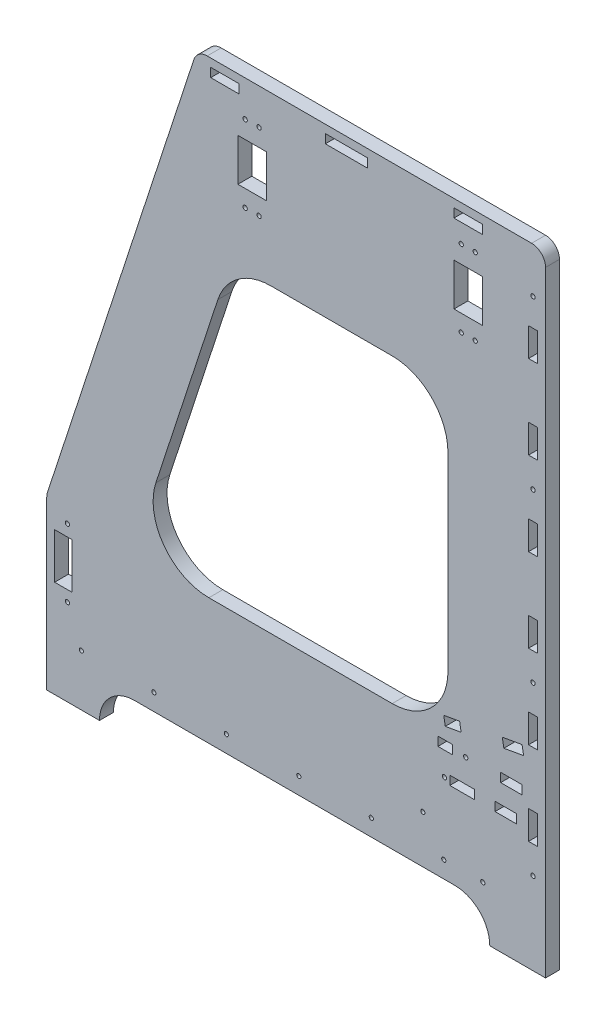
SolidWorks part; units mm, degrees
ref_plane "Płaszczyzna przednia" through (0, 0, 0) normal (0, 0, 1) x (1, 0, 0)
ref_plane "Płaszczyzna górna" through (0, 0, 0) normal (0, 1, 0) x (1, 0, 0)
ref_plane "Płaszczyzna prawa" through (0, 0, 0) normal (1, 0, 0) x (0, 0, -1)
ref_plane "Płaszczyzna1" through (0, 0, -20) normal (0, 0, 1) x (1, 0, 0)
sketch "Szkic1" plane through (0, 0, -20) normal (0, 0, 1) x (1, 0, 0)
  line L0 (-250.3685, -57.104) -> (-250.3685, -508.604)
  line L1 (-250.3685, -57.104) -> (-608.3685, -57.104)
  line L2 (-250.3685, -508.604) -> (-608.3685, -508.604)
  line L3 (-608.3685, -57.104) -> (-608.3685, -508.604)
  point P0 (0, 0)
  dimension "D1" = 358
  dimension "D2" = 451.5
  dimension "D3" = 250.3685
extrude "Dodanie-wyciągnięcie1" add sketch "Szkic1" along normal blind 10
sketch "Szkic2" plane through (0, 0, -20) normal (0, 0, -1) x (-1, 0, 0)
  line L0 (608.3685, -387.604) -> (502.6212, -63.9978)
  line L1 (608.3685, -57.104) -> (608.3685, -508.604) construction
  line L2 (500.3685, -57.104) -> (493.1159, -57.104)
  line L3 (250.3685, -57.104) -> (608.3685, -57.104) construction
  line L4 (500.3685, -57.104) -> (608.3685, -57.104)
  line L5 (608.3685, -57.104) -> (608.3685, -387.604)
  line L6 (250.3685, -508.604) -> (250.3685, -57.104) construction
  line L7 (608.3685, -508.604) -> (250.3685, -508.604) construction
  arc A0 (502.6212, -63.9978) -> (493.1159, -57.104) centre (493.1159, -67.104) ccw
  dimension "D3" = 10
  dimension "D1" = 250
  dimension "D2" = 121
  dimension "D4" = 71.904
extrude "Wytnij-wyciągnięcie1" cut sketch "Szkic2" against normal blind 10
sketch "Szkic3" plane through (0, 0, -10) normal (0, 0, 1) x (1, 0, 0)
  line L0 (-608.3685, -508.604) -> (-250.3685, -508.604) construction
  line L1 (-570.3685, -508.604) -> (-290.3685, -508.604)
  line L4 (-545.3685, -483.604) -> (-315.3685, -483.604)
  arc A0 (-570.3685, -508.604) -> (-545.3685, -483.604) centre (-545.3685, -508.604) cw
  arc A1 (-315.3685, -483.604) -> (-290.3685, -508.604) centre (-315.3685, -508.604) cw
extrude "Wytnij-wyciągnięcie2" cut sketch "Szkic3" against normal blind 10
sketch "Szkic4" plane through (0, 0, -10) normal (0, 0, 1) x (1, 0, 0)
  line L0 (-491.8908, -393.104) -> (-360.3685, -393.104)
  line L1 (-250.3685, -508.604) -> (-250.3685, -57.104) construction
  line L2 (-320.3685, -353.104) -> (-320.3685, -217.104)
  line L3 (-447.4491, -177.104) -> (-360.3685, -177.104)
  line L4 (-529.9123, -340.6794) -> (-485.4705, -204.6794)
  line L9 (-315.3685, -483.604) -> (-545.3685, -483.604) construction
  line L10 (-250.3685, -57.104) -> (-493.1159, -57.104) construction
  line L12 (-502.6212, -63.9978) -> (-608.3685, -387.604) construction
  arc A0 (-360.3685, -393.104) -> (-320.3685, -353.104) centre (-360.3685, -353.104) ccw
  arc A1 (-529.9123, -340.6794) -> (-491.8908, -393.104) centre (-491.8908, -353.104) ccw
  arc A2 (-320.3685, -217.104) -> (-360.3685, -177.104) centre (-360.3685, -217.104) ccw
  arc A3 (-485.4705, -204.6794) -> (-447.4491, -177.104) centre (-447.4491, -217.104) cw
  dimension "D5" = 40
  dimension "D1" = 70
  dimension "D2" = 90.5
  dimension "D3" = 120
  dimension "D4" = 60
extrude "Wytnij-wyciągnięcie3" cut sketch "Szkic4" against normal blind 10
sketch "Szkic5" plane through (0, 0, -10) normal (0, 0, 1) x (1, 0, 0)
  line L0 (-262.3685, -109.604) -> (-256.3685, -109.604)
  line L1 (-262.3685, -129.604) -> (-256.3685, -129.604)
  line L2 (-262.3685, -129.604) -> (-262.3685, -109.604)
  line L3 (-256.3685, -129.604) -> (-256.3685, -109.604)
  line L4 (-256.3685, -109.604) -> (-262.3685, -109.604)
  line L5 (-256.3685, -109.604) -> (-262.3685, -109.604)
  line L6 (-262.3685, -109.604) -> (-262.3685, -129.604)
  line L7 (-262.3685, -109.604) -> (-262.3685, -129.604)
  line L9 (-262.3685, -129.604) -> (-256.3685, -129.604)
  line L10 (-262.3685, -129.604) -> (-256.3685, -129.604)
  line L11 (-256.3685, -129.604) -> (-256.3685, -109.604)
  line L12 (-262.5685, -129.804) -> (-262.5685, -109.404)
  line L13 (-262.5685, -109.404) -> (-256.1685, -109.404)
  line L14 (-256.1685, -129.804) -> (-256.1685, -109.404)
  line L15 (-262.5685, -129.804) -> (-256.1685, -129.804)
  line L24 (-256.3685, -129.604) -> (-256.3685, -109.604)
  line L49 (-256.3685, -109.604) -> (-256.3685, -91.154) construction
  line L50 (-262.3685, -109.604) -> (-262.3685, -91.154) construction
  line L51 (-256.3685, -109.604) -> (-256.3685, -91.154)
  line L52 (-262.3685, -109.604) -> (-262.3685, -91.154)
  dimension "D1" = 0
  dimension "D4" = 0.2
sketch "Szkic8" plane through (0, 0, -10) normal (0, 0, 1) x (1, 0, 0)
  line L0 (-262.5685, -109.404) -> (-256.1685, -109.404) construction
  line L1 (-262.5685, -129.804) -> (-262.5685, -109.404) construction
  line L2 (-256.1685, -129.804) -> (-256.1685, -109.404) construction
  line L3 (-262.5685, -129.804) -> (-256.1685, -129.804) construction
  line L4 (-262.5685, -109.404) -> (-256.1685, -109.404)
  line L5 (-262.5685, -129.804) -> (-262.5685, -109.404)
  line L6 (-256.1685, -129.804) -> (-256.1685, -109.404)
  line L7 (-262.5685, -129.804) -> (-256.1685, -129.804)
extrude "Wytnij-wyciągnięcie4" cut sketch "Szkic8" against normal blind 10
pattern_linear "Szyk liniowy1" count 6 spacing 60 along (0, -1, 0) of "Wytnij-wyciągnięcie4"
sketch "Szkic33" plane through (0, 0, -10) normal (0, 0, 1) x (1, 0, 0)
  line L0 (-262.3685, -88.054) -> (-256.3685, -88.054) construction
  line L1 (-262.3685, -91.154) -> (-256.3685, -91.154) construction
  line L2 (-262.3685, -88.054) -> (-256.3685, -88.054)
  line L3 (-262.3685, -91.154) -> (-256.3685, -91.154)
  line L4 (-259.3685, -88.054) -> (-259.3685, -91.154)
  circle A0 centre (-259.3685, -89.604) radius 1.55
  dimension "D1" = 3.1
sketch "Szkic9" plane through (0, 0, -10) normal (0, 0, 1) x (1, 0, 0)
  circle A0 centre (-259.3685, -89.604) radius 1.55 construction
  circle A1 centre (-259.3685, -89.604) radius 1.55
extrude "Wytnij-wyciągnięcie5" cut sketch "Szkic9" against normal blind 10
pattern_linear "Szyk liniowy2" count 4 spacing 120 along (0, -1, 0) of "Wytnij-wyciągnięcie5"
sketch "Szkic11" plane through (0, 0, -10) normal (0, 0, 1) x (1, 0, 0)
  line L0 (-602.5685, -406.124) -> (-602.5685, -438.804)
  line L1 (-602.3685, -406.324) -> (-590.3685, -406.324)
  line L2 (-602.5685, -438.804) -> (-590.1685, -438.804)
  line L3 (-590.3685, -438.604) -> (-590.3685, -406.324) construction
  line L4 (-590.1685, -438.804) -> (-590.1685, -406.124)
  line L5 (-602.3685, -438.604) -> (-590.3685, -438.604)
  line L6 (-590.3685, -438.604) -> (-590.3685, -406.324)
  line L8 (-250.3685, -57.104) -> (-493.1159, -57.104)
  line L9 (-596.3685, -445.004) -> (-590.3685, -445.004) construction
  line L10 (-502.6212, -63.9978) -> (-608.3685, -387.604)
  line L11 (-608.3685, -387.604) -> (-608.3685, -508.604)
  line L12 (-608.3685, -508.604) -> (-570.3685, -508.604)
  line L13 (-545.3685, -483.604) -> (-315.3685, -483.604)
  line L14 (-290.3685, -508.604) -> (-250.3685, -508.604)
  line L15 (-250.3685, -508.604) -> (-250.3685, -57.104)
  line L16 (-250.3685, -57.104) -> (-493.1159, -57.104)
  line L17 (-590.3685, -448.104) -> (-596.3685, -448.104) construction
  line L18 (-502.6212, -63.9978) -> (-608.3685, -387.604)
  line L19 (-608.3685, -387.604) -> (-608.3685, -508.604)
  line L20 (-608.3685, -508.604) -> (-570.3685, -508.604)
  line L21 (-545.3685, -483.604) -> (-315.3685, -483.604)
  line L22 (-290.3685, -508.604) -> (-250.3685, -508.604)
  line L23 (-250.3685, -508.604) -> (-250.3685, -57.104)
  line L28 (-596.3685, -396.324) -> (-590.3685, -396.324) construction
  line L29 (-590.3685, -399.424) -> (-596.3685, -399.424) construction
  line L30 (-602.3685, -406.324) -> (-602.3685, -438.604)
  line L32 (-596.3685, -396.324) -> (-590.3685, -396.324)
  line L33 (-590.3685, -399.424) -> (-596.3685, -399.424)
  line L34 (-596.3685, -445.004) -> (-590.3685, -445.004)
  line L35 (-590.3685, -448.104) -> (-596.3685, -448.104)
  line L36 (-593.3685, -396.324) -> (-593.3685, -399.424)
  line L37 (-593.3685, -445.004) -> (-593.3685, -448.104)
  line L46 (-602.5685, -406.124) -> (-590.1685, -406.124)
  circle A1 centre (-593.3685, -397.874) radius 1.55
  circle A2 centre (-593.3685, -446.554) radius 1.55
  arc A6 (-545.3685, -483.604) -> (-570.3685, -508.604) centre (-545.3685, -508.604) ccw
  arc A7 (-290.3685, -508.604) -> (-315.3685, -483.604) centre (-315.3685, -508.604) ccw
  arc A10 (-545.3685, -483.604) -> (-570.3685, -508.604) centre (-545.3685, -508.604) ccw
  arc A11 (-290.3685, -508.604) -> (-315.3685, -483.604) centre (-315.3685, -508.604) ccw
  arc A17 (-493.1159, -57.104) -> (-502.6212, -63.9978) centre (-493.1159, -67.104) ccw
  arc A18 (-493.1159, -57.104) -> (-502.6212, -63.9978) centre (-493.1159, -67.104) ccw
  point P21 (-596.5685, -406.124)
  point P22 (-596.5685, -438.804)
  dimension "D3" = 3.1
  dimension "D4" = 3.1
  dimension "D2" = 12
  dimension "D1" = 0
sketch "Szkic12" plane through (0, 0, -10) normal (0, 0, 1) x (1, 0, 0)
  line L4 (-602.5685, -406.124) -> (-590.1685, -406.124) construction
  line L5 (-590.1685, -438.804) -> (-590.1685, -406.124) construction
  line L6 (-602.5685, -438.804) -> (-590.1685, -438.804) construction
  line L7 (-602.5685, -406.124) -> (-602.5685, -438.804) construction
  line L8 (-602.5685, -406.124) -> (-590.1685, -406.124)
  line L9 (-590.1685, -438.804) -> (-590.1685, -406.124)
  line L10 (-602.5685, -438.804) -> (-590.1685, -438.804)
  line L11 (-602.5685, -406.124) -> (-602.5685, -438.804)
extrude "Wytnij-wyciągnięcie7" cut sketch "Szkic12" against normal blind 10
sketch "Szkic13" plane through (0, 0, -10) normal (0, 0, 1) x (1, 0, 0)
  circle A1 centre (-593.3685, -397.874) radius 1.55 construction
  circle A2 centre (-593.3685, -446.554) radius 1.55 construction
  circle A3 centre (-593.3685, -397.874) radius 1.55
  circle A4 centre (-593.3685, -446.554) radius 1.55
extrude "Wytnij-wyciągnięcie8" cut sketch "Szkic13" against normal blind 10
sketch "Szkic15" plane through (0, 0, -10) normal (0, 0, 1) x (1, 0, 0)
  circle A0 centre (-295.3685, -471.604) radius 1.5 construction
  circle A1 centre (-323.3685, -471.604) radius 1.5 construction
  circle A2 centre (-375.3685, -471.604) radius 1.5 construction
  circle A3 centre (-427.3685, -471.604) radius 1.5 construction
  circle A4 centre (-531.3685, -471.604) radius 1.5 construction
  circle A5 centre (-479.3685, -471.604) radius 1.5 construction
  circle A6 centre (-583.3685, -471.604) radius 1.5 construction
  circle A7 centre (-338.3685, -449.4127) radius 1.5 construction
  circle A8 centre (-295.3685, -471.604) radius 1.5
  circle A9 centre (-323.3685, -471.604) radius 1.5
  circle A10 centre (-375.3685, -471.604) radius 1.5
  circle A11 centre (-427.3685, -471.604) radius 1.5
  circle A12 centre (-531.3685, -471.604) radius 1.5
  circle A13 centre (-479.3685, -471.604) radius 1.5
  circle A14 centre (-583.3685, -471.604) radius 1.5
  circle A15 centre (-338.3685, -449.4127) radius 1.5
extrude "Wytnij-wyciągnięcie9" cut sketch "Szkic15" against normal blind 10
sketch "Szkic16" plane through (0, 0, -10) normal (0, 0, 1) x (1, 0, 0)
  line L1 (-460.8685, -95.404) -> (-471.0685, -95.404)
  line L7 (-450.8685, -139.3649) -> (-460.8685, -139.3649) construction
  line L9 (-460.8685, -81.2649) -> (-470.8685, -81.2649) construction
  line L17 (-460.8685, -84.3649) -> (-470.8685, -84.3649) construction
  line L24 (-450.8685, -136.2649) -> (-460.8685, -136.2649) construction
  line L25 (-450.8685, -81.2649) -> (-460.8685, -81.2649) construction
  line L26 (-471.0685, -95.404) -> (-471.0685, -125.804)
  line L27 (-471.0685, -125.804) -> (-460.8685, -125.804)
  line L54 (-460.8685, -139.3649) -> (-470.8685, -139.3649) construction
  line L55 (-460.8685, -136.2649) -> (-470.8685, -136.2649) construction
  line L58 (-460.8685, -81.2649) -> (-470.8685, -81.2649)
  line L59 (-460.8685, -84.3649) -> (-470.8685, -84.3649)
  line L60 (-450.8685, -84.3649) -> (-460.8685, -84.3649) construction
  line L61 (-450.8685, -139.3649) -> (-460.8685, -139.3649)
  line L62 (-460.8685, -139.3649) -> (-470.8685, -139.3649)
  line L63 (-460.8685, -136.2649) -> (-470.8685, -136.2649)
  line L64 (-450.8685, -136.2649) -> (-460.8685, -136.2649)
  line L65 (-450.8685, -81.2649) -> (-460.8685, -81.2649)
  line L68 (-465.8685, -81.2649) -> (-465.8685, -84.3649)
  line L69 (-450.8685, -84.3649) -> (-460.8685, -84.3649)
  line L70 (-465.8685, -136.2649) -> (-465.8685, -139.3649)
  line L71 (-460.8724, -137.8039) -> (-460.8704, -125.804)
  line L77 (-460.8704, -95.404) -> (-460.8724, -107.404)
  line L78 (-455.8685, -81.2649) -> (-455.8685, -84.3649)
  line L80 (-460.8685, -125.604) -> (-460.8685, -95.604)
  line L81 (-460.8685, -95.604) -> (-470.8685, -95.604)
  line L82 (-470.8685, -95.604) -> (-470.8685, -125.604)
  line L83 (-470.8685, -125.604) -> (-460.8685, -125.604)
  line L85 (-460.8685, -95.604) -> (-470.8685, -95.604)
  line L86 (-470.8685, -95.604) -> (-470.8685, -125.604)
  line L87 (-470.8685, -125.604) -> (-460.8685, -125.604)
  line L88 (-450.8685, -95.604) -> (-460.8685, -95.604) construction
  line L89 (-450.8685, -95.604) -> (-450.8685, -125.604) construction
  line L90 (-450.8685, -125.604) -> (-460.8685, -125.604) construction
  line L129 (-450.8685, -95.604) -> (-460.8685, -95.604)
  line L130 (-450.8685, -95.604) -> (-450.8685, -125.604)
  line L131 (-450.8685, -125.604) -> (-460.8685, -125.604)
  line L132 (-455.8685, -136.2649) -> (-455.8685, -139.3649)
  line L133 (-450.6685, -125.804) -> (-460.8685, -125.804)
  line L134 (-450.6685, -95.404) -> (-450.6685, -125.804)
  line L135 (-450.6685, -95.404) -> (-460.8685, -95.404)
  circle A4 centre (-465.8685, -82.8149) radius 1.55
  circle A6 centre (-465.8685, -137.8149) radius 1.55
  circle A8 centre (-455.8685, -137.8149) radius 1.55
  circle A9 centre (-455.8685, -82.8149) radius 1.55
  point P26 (-450.4685, -138.0079)
  point P27 (-450.4685, -107.2)
  dimension "D1" = 3.1
  dimension "D5" = 3.1
  dimension "D6" = 3.1
  dimension "D13" = 3.1
  dimension "D2" = 0.2
  dimension "D11" = 0
  dimension "D12" = 0.2
sketch "Szkic17" plane through (0, 0, -10) normal (0, 0, 1) x (1, 0, 0)
  line L0 (-471.0685, -125.804) -> (-460.8685, -125.804) construction
  line L1 (-450.6685, -125.804) -> (-460.8685, -125.804) construction
  line L2 (-450.6685, -95.404) -> (-450.6685, -125.804) construction
  line L4 (-471.0685, -95.404) -> (-471.0685, -125.804) construction
  line L6 (-460.8685, -95.404) -> (-471.0685, -95.404) construction
  line L7 (-450.6685, -95.404) -> (-460.8685, -95.404) construction
  line L8 (-471.0685, -125.804) -> (-460.8685, -125.804)
  line L9 (-450.6685, -125.804) -> (-460.8685, -125.804)
  line L10 (-471.0685, -95.404) -> (-471.0685, -125.804)
  line L11 (-450.6685, -95.404) -> (-450.6685, -125.804)
  line L15 (-460.8685, -95.404) -> (-471.0685, -95.404)
  line L16 (-450.6685, -95.404) -> (-460.8685, -95.404)
  circle A0 centre (-455.8685, -137.8149) radius 1.55 construction
  circle A1 centre (-455.8685, -82.8149) radius 1.55 construction
  circle A2 centre (-455.8685, -137.8149) radius 1.55
  circle A3 centre (-455.8685, -82.8149) radius 1.55
  circle A11 centre (-465.8685, -137.8149) radius 1.55
  circle A12 centre (-465.8685, -137.8149) radius 1.55
  circle A15 centre (-465.8685, -82.8149) radius 1.55
  circle A16 centre (-465.8685, -82.8149) radius 1.55
  dimension "D12" = 0
  dimension "D14" = 0
extrude "Wytnij-wyciągnięcie10" cut sketch "Szkic17" against normal blind 10
sketch "Szkic18" plane through (0, 0, -10) normal (0, 0, 1) x (1, 0, 0)
  line L4 (-408.1185, -63.104) -> (-408.1185, -69.104) construction
  line L5 (-408.1185, -69.104) -> (-378.1185, -69.104) construction
  line L6 (-378.1185, -69.104) -> (-378.1185, -63.104) construction
  line L7 (-378.1185, -63.104) -> (-408.1185, -63.104) construction
  line L8 (-470.3685, -69.104) -> (-470.3685, -63.104)
  line L9 (-470.3685, -63.104) -> (-490.3685, -63.104)
  line L10 (-490.3685, -63.104) -> (-490.3685, -69.104)
  line L11 (-490.3685, -69.104) -> (-470.3685, -69.104)
  line L28 (-470.3685, -69.104) -> (-470.3685, -63.104)
  line L29 (-470.3685, -63.104) -> (-490.3685, -63.104)
  line L30 (-490.3685, -63.104) -> (-490.3685, -69.104)
  line L43 (-490.3685, -69.104) -> (-470.3685, -69.104)
  line L44 (-315.8685, -63.104) -> (-315.8685, -69.104) construction
  line L45 (-315.8685, -69.104) -> (-295.8685, -69.104) construction
  line L46 (-295.8685, -69.104) -> (-295.8685, -63.104) construction
  line L47 (-295.8685, -63.104) -> (-315.8685, -63.104) construction
  line L48 (-408.1185, -63.104) -> (-408.1185, -69.104)
  line L49 (-408.1185, -69.104) -> (-378.1185, -69.104)
  line L50 (-378.1185, -69.104) -> (-378.1185, -63.104)
  line L51 (-378.1185, -63.104) -> (-408.1185, -63.104)
  line L56 (-315.8685, -63.104) -> (-315.8685, -69.104)
  line L57 (-315.8685, -69.104) -> (-295.8685, -69.104)
  line L58 (-295.8685, -69.104) -> (-295.8685, -63.104)
  line L59 (-295.8685, -63.104) -> (-315.8685, -63.104)
  line L64 (-408.3185, -69.304) -> (-377.9185, -69.304)
  line L65 (-377.9185, -69.304) -> (-377.9185, -62.904)
  line L66 (-377.9185, -62.904) -> (-408.3185, -62.904)
  line L67 (-408.3185, -62.904) -> (-408.3185, -69.304)
  line L68 (-316.0685, -69.304) -> (-295.6685, -69.304)
  line L69 (-295.6685, -69.304) -> (-295.6685, -62.904)
  line L70 (-295.6685, -62.904) -> (-316.0685, -62.904)
  line L71 (-316.0685, -62.904) -> (-316.0685, -69.304)
  line L72 (-490.5685, -69.304) -> (-470.1685, -69.304)
  line L73 (-470.1685, -69.304) -> (-470.1685, -62.904)
  line L74 (-470.1685, -62.904) -> (-490.5685, -62.904)
  line L75 (-490.5685, -62.904) -> (-490.5685, -69.304)
  dimension "D3" = 0.2
  dimension "D2" = 0
sketch "Szkic19" plane through (0, 0, -10) normal (0, 0, 1) x (1, 0, 0)
  line L0 (-470.1685, -62.904) -> (-490.5685, -62.904) construction
  line L1 (-490.5685, -62.904) -> (-490.5685, -69.304) construction
  line L2 (-490.5685, -69.304) -> (-470.1685, -69.304) construction
  line L3 (-470.1685, -69.304) -> (-470.1685, -62.904) construction
  line L4 (-408.3185, -69.304) -> (-377.9185, -69.304) construction
  line L5 (-377.9185, -69.304) -> (-377.9185, -62.904) construction
  line L6 (-377.9185, -62.904) -> (-408.3185, -62.904) construction
  line L7 (-408.3185, -62.904) -> (-408.3185, -69.304) construction
  line L8 (-316.0685, -69.304) -> (-295.6685, -69.304) construction
  line L9 (-295.6685, -69.304) -> (-295.6685, -62.904) construction
  line L10 (-295.6685, -62.904) -> (-316.0685, -62.904) construction
  line L11 (-316.0685, -62.904) -> (-316.0685, -69.304) construction
  line L24 (-470.1685, -62.904) -> (-490.5685, -62.904)
  line L25 (-490.5685, -62.904) -> (-490.5685, -69.304)
  line L26 (-490.5685, -69.304) -> (-470.1685, -69.304)
  line L27 (-470.1685, -69.304) -> (-470.1685, -62.904)
  line L28 (-408.3185, -69.304) -> (-377.9185, -69.304)
  line L29 (-377.9185, -69.304) -> (-377.9185, -62.904)
  line L30 (-377.9185, -62.904) -> (-408.3185, -62.904)
  line L31 (-408.3185, -62.904) -> (-408.3185, -69.304)
  line L32 (-316.0685, -69.304) -> (-295.6685, -69.304)
  line L33 (-295.6685, -69.304) -> (-295.6685, -62.904)
  line L34 (-295.6685, -62.904) -> (-316.0685, -62.904)
  line L35 (-316.0685, -62.904) -> (-316.0685, -69.304)
extrude "Wytnij-wyciągnięcie11" cut sketch "Szkic19" against normal blind 10
sketch "Szkic22" plane through (0, 0, -10) normal (0, 0, 1) x (1, 0, 0)
  line L4 (-271.3685, -423.104) -> (-271.3685, -417.104) construction
  line L5 (-271.3685, -417.104) -> (-286.3685, -417.104) construction
  line L6 (-286.3685, -417.104) -> (-286.3685, -423.104) construction
  line L7 (-286.3685, -423.104) -> (-271.3685, -423.104) construction
  line L8 (-318.8685, -417.104) -> (-301.3685, -417.104) construction
  line L9 (-318.8685, -423.104) -> (-318.8685, -417.104) construction
  line L10 (-318.8685, -423.104) -> (-301.3685, -423.104) construction
  line L11 (-301.3685, -423.104) -> (-301.3685, -417.104) construction
  line L12 (-271.3685, -423.104) -> (-271.3685, -417.104)
  line L13 (-271.3685, -417.104) -> (-286.3685, -417.104)
  line L14 (-286.3685, -417.104) -> (-286.3685, -423.104)
  line L15 (-286.3685, -423.104) -> (-271.3685, -423.104)
  line L20 (-271.1685, -423.304) -> (-271.1685, -416.904)
  line L21 (-271.1685, -416.904) -> (-286.5685, -416.904)
  line L22 (-286.5685, -416.904) -> (-286.5685, -423.304)
  line L23 (-286.5685, -423.304) -> (-271.1685, -423.304)
  line L26 (-318.8685, -417.104) -> (-301.3685, -417.104)
  line L27 (-318.8685, -423.104) -> (-318.8685, -417.104)
  line L28 (-318.8685, -423.104) -> (-301.3685, -423.104)
  line L29 (-301.3685, -423.104) -> (-301.3685, -417.104)
  line L30 (-319.0685, -416.904) -> (-301.1685, -416.904)
  line L31 (-301.1685, -423.304) -> (-301.1685, -416.904)
  line L32 (-319.0685, -423.304) -> (-301.1685, -423.304)
  line L33 (-319.0685, -423.304) -> (-319.0685, -416.904)
  line L34 (-321.3185, -423.104) -> (-321.3185, -417.104) construction
  line L35 (-324.4185, -423.104) -> (-324.4185, -417.104) construction
  line L36 (-321.3185, -423.104) -> (-321.3185, -417.104)
  line L37 (-324.4185, -423.104) -> (-324.4185, -417.104)
  line L38 (-321.3185, -420.104) -> (-324.4185, -420.104)
  circle A1 centre (-322.8685, -420.104) radius 1.55
  point P0 (-318.4685, -416.4043)
  point P1 (-318.4685, -428.6043)
  point P9 (-318.6685, -416.2043)
  point P10 (-318.6685, -428.8043)
  point P11 (-318.4685, -416.4043)
  point P27 (-318.4685, -428.6043)
  dimension "D2" = 0.2
  dimension "D4" = 3.1
  dimension "D1" = 0.2
sketch "Szkic23" plane through (0, 0, -10) normal (0, 0, 1) x (1, 0, 0)
  line L4 (-286.5685, -416.904) -> (-286.5685, -423.304) construction
  line L5 (-286.5685, -423.304) -> (-271.1685, -423.304) construction
  line L6 (-271.1685, -423.304) -> (-271.1685, -416.904) construction
  line L7 (-271.1685, -416.904) -> (-286.5685, -416.904) construction
  line L8 (-319.0685, -416.904) -> (-301.1685, -416.904) construction
  line L9 (-319.0685, -423.304) -> (-319.0685, -416.904) construction
  line L10 (-319.0685, -423.304) -> (-301.1685, -423.304) construction
  line L11 (-301.1685, -423.304) -> (-301.1685, -416.904) construction
  line L12 (-286.5685, -416.904) -> (-286.5685, -423.304)
  line L13 (-286.5685, -423.304) -> (-271.1685, -423.304)
  line L14 (-271.1685, -423.304) -> (-271.1685, -416.904)
  line L15 (-271.1685, -416.904) -> (-286.5685, -416.904)
  line L16 (-319.0685, -416.904) -> (-301.1685, -416.904)
  line L17 (-319.0685, -423.304) -> (-319.0685, -416.904)
  line L18 (-319.0685, -423.304) -> (-301.1685, -423.304)
  line L19 (-301.1685, -423.304) -> (-301.1685, -416.904)
  circle A1 centre (-322.8685, -420.104) radius 1.55 construction
  circle A2 centre (-322.8685, -420.104) radius 1.55
extrude "Wytnij-wyciągnięcie12" cut sketch "Szkic23" against normal blind 10
sketch "Szkic27" plane through (0, 0, -10) normal (0, 0, 1) x (1, 0, 0)
  line L0 (-311.1316, -386.0398) -> (-312.1735, -380.131) construction
  line L1 (-312.1735, -380.131) -> (-323.1714, -382.0702) construction
  line L3 (-322.1295, -387.9791) -> (-311.1316, -386.0398) construction
  line L4 (-266.3229, -378.1389) -> (-267.3648, -372.23) construction
  line L5 (-267.3648, -372.23) -> (-281.1521, -374.6611) construction
  line L6 (-281.1521, -374.6611) -> (-280.1102, -380.5699) construction
  line L7 (-280.1102, -380.5699) -> (-266.3229, -378.1389) construction
  line L8 (-311.1316, -386.0398) -> (-312.1735, -380.131)
  line L9 (-312.1735, -380.131) -> (-323.1714, -382.0702)
  line L11 (-322.1295, -387.9791) -> (-311.1316, -386.0398)
  line L12 (-266.3229, -378.1389) -> (-267.3648, -372.23)
  line L13 (-267.3648, -372.23) -> (-281.1521, -374.6611)
  line L14 (-281.1521, -374.6611) -> (-280.1102, -380.5699)
  line L15 (-280.1102, -380.5699) -> (-266.3229, -378.1389)
  line L16 (-312.0113, -379.8993) -> (-323.4031, -381.908)
  line L17 (-323.4031, -381.908) -> (-322.2918, -388.2108)
  line L18 (-322.2918, -388.2108) -> (-310.8999, -386.2021)
  line L19 (-310.8999, -386.2021) -> (-312.0113, -379.8993)
  line L20 (-267.2025, -371.9983) -> (-281.3838, -374.4988)
  line L21 (-281.3838, -374.4988) -> (-280.2724, -380.8016)
  line L22 (-280.2724, -380.8016) -> (-266.0912, -378.3011)
  line L23 (-266.0912, -378.3011) -> (-267.2025, -371.9983)
  line L24 (-323.1714, -382.0702) -> (-322.1295, -387.9791) construction
  dimension "D1" = 0.2
sketch "Szkic29" plane through (0, 0, -10) normal (0, 0, 1) x (1, 0, 0)
  line L0 (-323.4031, -381.908) -> (-322.2918, -388.2108) construction
  line L1 (-322.2918, -388.2108) -> (-310.8999, -386.2021) construction
  line L2 (-310.8999, -386.2021) -> (-312.0113, -379.8993) construction
  line L3 (-312.0113, -379.8993) -> (-323.4031, -381.908) construction
  line L4 (-281.3838, -374.4988) -> (-280.2724, -380.8016) construction
  line L5 (-280.2724, -380.8016) -> (-266.0912, -378.3011) construction
  line L6 (-266.0912, -378.3011) -> (-267.2025, -371.9983) construction
  line L7 (-267.2025, -371.9983) -> (-281.3838, -374.4988) construction
  line L8 (-323.4031, -381.908) -> (-322.2918, -388.2108)
  line L9 (-322.2918, -388.2108) -> (-310.8999, -386.2021)
  line L10 (-310.8999, -386.2021) -> (-312.0113, -379.8993)
  line L11 (-312.0113, -379.8993) -> (-323.4031, -381.908)
  line L12 (-281.3838, -374.4988) -> (-280.2724, -380.8016)
  line L13 (-280.2724, -380.8016) -> (-266.0912, -378.3011)
  line L14 (-266.0912, -378.3011) -> (-267.2025, -371.9983)
  line L15 (-267.2025, -371.9983) -> (-281.3838, -374.4988)
extrude "Wytnij-wyciągnięcie14" cut sketch "Szkic29" against normal blind 10
sketch "Szkic31" plane through (0, 0, -10) normal (0, 0, 1) x (1, 0, 0)
  line L0 (-327.3685, -397.104) -> (-317.3685, -397.104) construction
  line L1 (-327.3685, -403.104) -> (-327.3685, -397.104) construction
  line L2 (-327.3685, -403.104) -> (-317.3685, -403.104) construction
  line L3 (-317.3685, -403.104) -> (-317.3685, -397.104) construction
  line L4 (-282.3685, -403.104) -> (-282.3685, -397.104) construction
  line L5 (-282.3685, -397.104) -> (-267.3685, -397.104) construction
  line L6 (-282.3685, -403.104) -> (-267.3685, -403.104) construction
  line L7 (-267.3685, -403.104) -> (-267.3685, -397.104) construction
  line L8 (-327.3685, -397.104) -> (-317.3685, -397.104)
  line L9 (-327.3685, -403.104) -> (-327.3685, -397.104)
  line L10 (-327.3685, -403.104) -> (-317.3685, -403.104)
  line L11 (-317.3685, -403.104) -> (-317.3685, -397.104)
  line L12 (-282.3685, -403.104) -> (-282.3685, -397.104)
  line L13 (-282.3685, -397.104) -> (-267.3685, -397.104)
  line L14 (-282.3685, -403.104) -> (-267.3685, -403.104)
  line L15 (-267.3685, -403.104) -> (-267.3685, -397.104)
  line L16 (-306.1002, -403.104) -> (-306.1002, -397.104) construction
  line L17 (-309.2002, -403.104) -> (-309.2002, -397.104) construction
  line L18 (-306.1002, -403.104) -> (-306.1002, -397.104)
  line L19 (-309.2002, -403.104) -> (-309.2002, -397.104)
  line L20 (-309.2002, -400.104) -> (-306.1002, -400.104)
  line L21 (-327.5685, -396.904) -> (-317.1685, -396.904)
  line L22 (-317.1685, -403.304) -> (-317.1685, -396.904)
  line L23 (-327.5685, -403.304) -> (-317.1685, -403.304)
  line L24 (-327.5685, -403.304) -> (-327.5685, -396.904)
  line L25 (-282.5685, -403.304) -> (-282.5685, -396.904)
  line L26 (-282.5685, -396.904) -> (-267.1685, -396.904)
  line L27 (-267.1685, -403.304) -> (-267.1685, -396.904)
  line L28 (-282.5685, -403.304) -> (-267.1685, -403.304)
  circle A0 centre (-307.6502, -400.104) radius 1.55
  dimension "D1" = 3.1
  dimension "D2" = 0.2
sketch "Szkic32" plane through (0, 0, -10) normal (0, 0, 1) x (1, 0, 0)
  line L0 (-327.5685, -396.904) -> (-317.1685, -396.904) construction
  line L1 (-317.1685, -403.304) -> (-317.1685, -396.904) construction
  line L2 (-327.5685, -403.304) -> (-317.1685, -403.304) construction
  line L3 (-327.5685, -403.304) -> (-327.5685, -396.904) construction
  line L4 (-282.5685, -403.304) -> (-282.5685, -396.904) construction
  line L5 (-282.5685, -396.904) -> (-267.1685, -396.904) construction
  line L6 (-267.1685, -403.304) -> (-267.1685, -396.904) construction
  line L7 (-282.5685, -403.304) -> (-267.1685, -403.304) construction
  line L8 (-327.5685, -396.904) -> (-317.1685, -396.904)
  line L9 (-317.1685, -403.304) -> (-317.1685, -396.904)
  line L10 (-327.5685, -403.304) -> (-317.1685, -403.304)
  line L11 (-327.5685, -403.304) -> (-327.5685, -396.904)
  line L12 (-282.5685, -403.304) -> (-282.5685, -396.904)
  line L13 (-282.5685, -396.904) -> (-267.1685, -396.904)
  line L14 (-267.1685, -403.304) -> (-267.1685, -396.904)
  line L15 (-282.5685, -403.304) -> (-267.1685, -403.304)
  circle A0 centre (-307.6502, -400.104) radius 1.55 construction
  circle A1 centre (-307.6502, -400.104) radius 1.55
extrude "Wytnij-wyciągnięcie15" cut sketch "Szkic32" against normal blind 10
sketch "Szkic34" plane through (0, 0, -20) normal (0, 0, -1) x (-1, 0, 0)
  line L0 (607.2813, -383.6763) -> (608.3685, -387.604)
  line L2 (608.3685, -387.604) -> (608.3685, -391.6793)
  arc A0 (608.3685, -391.6793) -> (607.2813, -383.6763) centre (578.3685, -391.6793) ccw
  dimension "D1" = 30
extrude "Wytnij-wyciągnięcie16" cut sketch "Szkic34" against normal blind 10
pattern_linear "Szyk liniowy3" count 2 spacing 155 along (1, 0, 0) of "Wytnij-wyciągnięcie10"
sketch "Szkic35" plane through (0, 0, -10) normal (0, 0, 1) x (1, 0, 0)
  line L5 (-260.3685, -57.104) -> (-250.3685, -57.104)
  line L6 (-250.3685, -57.104) -> (-250.3685, -67.104)
  arc A0 (-250.3685, -67.104) -> (-260.3685, -57.104) centre (-260.3685, -67.104) ccw
  point P10 (-250.3685, -57.104)
  dimension "D1" = 10
extrude "Wytnij-wyciągnięcie17" cut sketch "Szkic35" against normal blind 10
equation "\"tolerancja_wpusy\"=0.2"
equation "\"D4@Szkic5\"=\"tolerancja_wpusy\""
equation "\"dlugosc_wpustu_duzy\"=20"
equation "\"srednica_otworu_M3\"=3.1"
equation "\"szerokosc_nogi_T\"=3.1"
equation "\"dlugosc_T_30\"=11"
equation "\"grubosc_na_nakretke_kwadrat\"=2"
equation "\"szerokosc_na_nakretke_kwadrat\"=5.85"
equation "\"wyokosc_nadstawki_T\"=0.5"
equation "\"D3@Szkic11\" = \"srednica_otworu_M3\""
equation "\"D2@Szkic16\"=\"tolerancja_wpusy\""
equation "\"D1@Szkic16\" = \"srednica_otworu_M3\""
equation "\"D5@Szkic16\"=\"srednica_otworu_M3\""
equation "\"D4@Szkic22\" = \"srednica_otworu_M3\""
equation "\"D1@Szkic31\"=\"srednica_otworu_M3\""
equation "\"D1@Szkic33\"=\"srednica_otworu_M3\""
